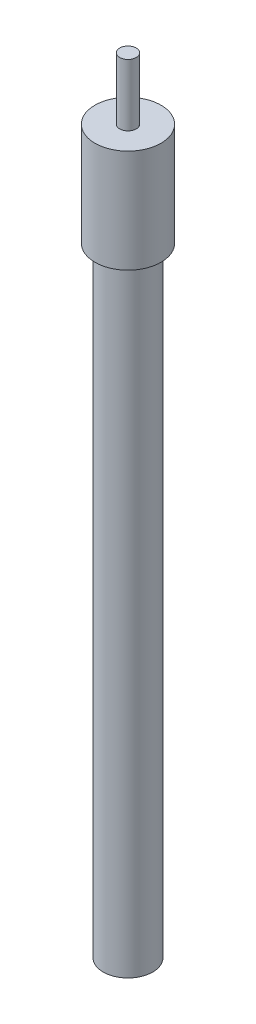
SolidWorks part; units mm, degrees
material "Glass"
ref_plane "Front Plane" through (0, 0, 0) normal (0, 0, 1) x (1, 0, 0)
ref_plane "Top Plane" through (0, 0, 0) normal (0, 1, 0) x (1, 0, 0)
ref_plane "Right Plane" through (0, 0, 0) normal (1, 0, 0) x (0, 0, -1)
other "Configuration Table"
sketch "Sketch1" plane through (0, 0, 0) normal (0, 1, 0) x (1, 0, 0)
  circle A0 centre (0, 0) radius 6
  dimension "D1" = 12
extrude "Electrode_Body" add sketch "Sketch1" along normal blind 150
sketch "Sketch2" plane through (0, 0, 0) normal (0, 1, 0) x (1, 0, 0)
  circle A0 centre (0, 0) radius 8
  dimension "D1" = 16
extrude "Cap" add sketch "Sketch2" along normal blind 25 from offset 150
sketch "Sketch3" plane through (0, 0, 0) normal (0, 1, 0) x (1, 0, 0)
  circle A0 centre (0, 0) radius 2
  dimension "D1" = 4
extrude "Cable_Stub" add sketch "Sketch3" along normal blind 15 from offset 175
sketch "Sketch4" plane through (0, 0, 0) normal (0, 1, 0) x (1, 0, 0)
  circle A0 centre (0, 0) radius 2
  dimension "D1" = 4
extrude "Platinum_Tip" add sketch "Sketch4" along normal blind 1.5
equation "\"Jar_OD\"= 90  'ASSUMED - Part G fallback - jar outer diameter"
equation "\"Jar_H\"= 120  'ASSUMED - Part G fallback - jar height"
equation "\"Pump_L\"= 45  'ASSUMED - Part G fallback"
equation "\"Pump_W\"= 24  'ASSUMED - Part G fallback"
equation "\"Pump_H\"= 33  'ASSUMED - Part G fallback"
equation "\"Pump_Outlet_OD\"= 7.5  'ASSUMED - Part G fallback"
equation "\"Tube_OD\"= 8  'ASSUMED - Part G fallback"
equation "\"Tube_ID\"= 6  'ASSUMED - Part G fallback"
equation "\"TDS_Body_Dia\"= 12  'ASSUMED - Part G fallback"
equation "\"TDS_Wet_Len\"= 45  'ASSUMED - Part G fallback - length in water"
equation "\"DS_Tube_Dia\"= 6  'ASSUMED - Part G fallback"
equation "\"DS_Tube_Len\"= 50  'ASSUMED - Part G fallback"
equation "\"ORP_Body_Dia\"= 12  'ASSUMED - Part G fallback"
equation "\"ORP_Body_Len\"= 150  'ASSUMED - Part G fallback"
equation "\"ORP_Cap_Dia\"= 16  'ASSUMED - Part G fallback"
equation "\"Turb_W\"= 33  'ASSUMED - Part G fallback - head width"
equation "\"Turb_D\"= 28  'ASSUMED - Part G fallback - head depth"
equation "\"Turb_H\"= 30  'ASSUMED - Part G fallback - head height"
equation "\"Turb_Slot_W\"= 10  'ASSUMED - Part G fallback - slot width"
equation "\"Flow_L\"= 62  'ASSUMED - Part G fallback YF-S201"
equation "\"Flow_W\"= 36  'ASSUMED - Part G fallback"
equation "\"Flow_H\"= 35  'ASSUMED - Part G fallback"
equation "\"Thread_G12_OD\"= 20.955  'ASSUMED - Part G fallback thread G1/2 (major diameter)"
equation "\"Valve_L\"= 75  'ASSUMED - Part G fallback"
equation "\"Valve_W\"= 45  'ASSUMED - Part G fallback"
equation "\"Valve_H\"= 60  'ASSUMED - Part G fallback"
equation "\"Tee_L\"= 40  'ASSUMED - Part G fallback - overall length"
equation "\"Tee_Branch_L\"= 25  'ASSUMED - Part G fallback"
equation "\"Tee_OD\"= 12  'ASSUMED - Part G fallback"
equation "\"Cuv_W\"= 12.5  'ASSUMED - old R3 cuvette (station suppressed in SS4)"
equation "\"Cuv_D\"= 12.5  'ASSUMED - old R3 cuvette (station suppressed in SS4)"
equation "\"Cuv_H\"= 45  'ASSUMED - old R3 cuvette (station suppressed in SS4)"
equation "\"LED_Board_L\"= 20  'ASSUMED - Part G fallback"
equation "\"LED_Board_W\"= 20  'ASSUMED - Part G fallback - LED at centre"
equation "\"GUVA_L\"= 20  'ASSUMED - Part G fallback"
equation "\"GUVA_W\"= 12  'ASSUMED - Part G fallback - sensor at centre"
equation "\"Reed_L\"= 27  'ASSUMED - Part G fallback MC-38 half"
equation "\"Reed_W\"= 14  'ASSUMED - Part G fallback"
equation "\"Reed_H\"= 8  'ASSUMED - Part G fallback"
equation "\"ESP_L\"= 51  'ASSUMED - Part G fallback"
equation "\"ESP_W\"= 28  'ASSUMED - Part G fallback"
equation "\"TFT_L\"= 58  'ASSUMED - Part G fallback - board"
equation "\"TFT_W\"= 35  'ASSUMED - Part G fallback - board"
equation "\"TFT_Win_L\"= 35  'ASSUMED - Part G fallback - visible window"
equation "\"TFT_Win_W\"= 28  'ASSUMED - Part G fallback - visible window"
equation "\"Relay_L\"= 50  'ASSUMED - Part G fallback"
equation "\"Relay_W\"= 26  'ASSUMED - Part G fallback"
equation "\"Relay_H\"= 19  'ASSUMED - Part G fallback"
equation "\"Mosfet_L\"= 34  'ASSUMED - Part G fallback"
equation "\"Mosfet_W\"= 17  'ASSUMED - Part G fallback"
equation "\"Mosfet_H\"= 12  'ASSUMED - Part G fallback"
equation "\"TDS_Board_L\"= 42  'ASSUMED - Part G fallback"
equation "\"TDS_Board_W\"= 32  'ASSUMED - Part G fallback"
equation "\"Turb_Board_L\"= 38  'ASSUMED - Part G fallback"
equation "\"Turb_Board_W\"= 28  'ASSUMED - Part G fallback"
equation "\"BNC_Thread_Dia\"= 9.5  'ASSUMED - Part G fallback"
equation "\"Plate_L\"= 420  'ASSUMED - Part G fallback"
equation "\"Plate_W\"= 297  'ASSUMED - Part G fallback"
equation "\"Plate_T\"= 6  'ASSUMED - Part G fallback"
equation "\"Probe_Clr\"= 0.3  'DESIGN VALUE - Part C rule 3 - printed probe hole = diameter + 0.3"
equation "\"Cuv_Clr\"= 0.2  'DESIGN VALUE - Part C rule 3 - cuvette pocket = size + 0.2"
equation "\"Label_H\"= 0.6  'DESIGN VALUE - Part D - raised label height"
equation "\"D1@Sketch1\" = \"ORP_Body_Dia\""
equation "\"D1@Electrode_Body\" = \"ORP_Body_Len\""
equation "\"D1@Sketch2\" = \"ORP_Cap_Dia\""
equation "\"Booster_L\"= 150  'ASSUMED - Part G fallback - booster pump"
equation "\"Booster_W\"= 95  'ASSUMED - Part G fallback"
equation "\"Booster_H\"= 100  'ASSUMED - Part G fallback"
equation "\"PTube_OD\"= 6.35  'ASSUMED - Part G fallback - product tube 1/4 inch"
equation "\"Qz_Out\"= 12  'ASSUMED - Part G fallback - quartz channel outside square"
equation "\"Qz_Path\"= 10  'ASSUMED - Part G fallback - quartz channel inside light path"
equation "\"Qz_L\"= 40  'ASSUMED - Part G fallback - quartz channel length"
equation "\"LED860_Dia\"= 5  'ASSUMED - Part G fallback - 860 nm LED"
equation "\"BPW_L\"= 5.4  'ASSUMED - Part G fallback - BPW34"
equation "\"BPW_W\"= 4.3  'ASSUMED - Part G fallback - BPW34"
equation "\"Cart_Dia\"= 50  'ASSUMED - Part G fallback - sediment and pre-carbon cartridges"
equation "\"Cart_L\"= 255  'ASSUMED - Part G fallback"
equation "\"UF_Dia\"= 50  'ASSUMED - Part G fallback - UF cartridge"
equation "\"UF_L\"= 260  'ASSUMED - Part G fallback"
equation "\"RO_Dia\"= 62  'ASSUMED - Part G fallback - RO membrane housing"
equation "\"RO_L\"= 300  'ASSUMED - Part G fallback"
equation "\"UVC_Dia\"= 40  'ASSUMED - Part G fallback - UV-C chamber"
equation "\"UVC_L\"= 300  'ASSUMED - Part G fallback"
equation "\"Tank_W\"= 260  'ASSUMED - Part G fallback - storage tank"
equation "\"Tank_D\"= 160  'ASSUMED - Part G fallback"
equation "\"Tank_H\"= 300  'ASSUMED - Part G fallback"
equation "\"Cab_W\"= 400  'ASSUMED - Part G fallback - purifier cabinet"
equation "\"Cab_D\"= 270  'ASSUMED - Part G fallback"
equation "\"Cab_H\"= 560  'ASSUMED - Part G fallback"
equation "\"ORP_Board_L\"= 40  'ASSUMED - Part G fallback - ORP buffer board"
equation "\"ORP_Board_W\"= 30  'ASSUMED - Part G fallback"
equation "\"Opt_Board_L\"= 50  'ASSUMED - Part G fallback - optical front-end board"
equation "\"Opt_Board_W\"= 40  'ASSUMED - Part G fallback"
equation "\"Buck_L\"= 43  'ASSUMED - Part G fallback - 12 V to 5 V buck module"
equation "\"Buck_W\"= 21  'ASSUMED - Part G fallback"
equation "\"Buck_H\"= 14  'ASSUMED - Part G fallback"
equation "\"BB_L\"= 165  'ASSUMED - Part G fallback - breadboard (As_Built_R3 only)"
equation "\"BB_W\"= 55  'ASSUMED - Part G fallback"
equation "\"BB_H\"= 10  'ASSUMED - Part G fallback"
